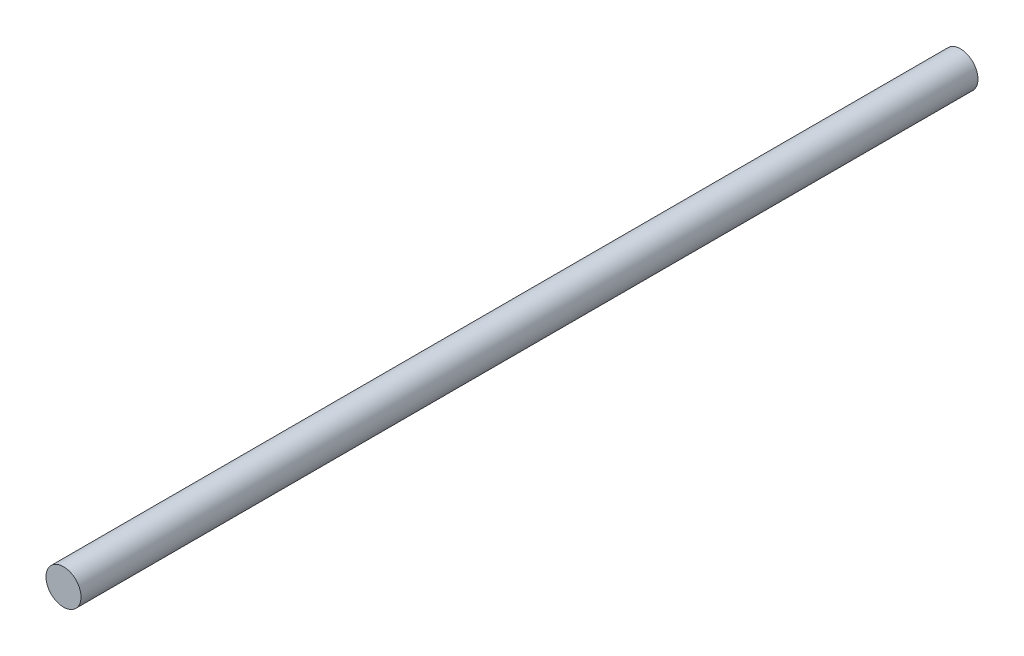
SolidWorks part; units mm, degrees
ref_plane "Alzado" through (0, 0, 0) normal (0, 0, 1) x (1, 0, 0)
ref_plane "Planta" through (0, 0, 0) normal (0, 1, 0) x (1, 0, 0)
ref_plane "Vista lateral" through (0, 0, 0) normal (1, 0, 0) x (0, 0, -1)
sketch "Croquis1" plane through (0, 0, 0) normal (0, 0, 1) x (1, 0, 0)
  circle A0 centre (0, 0) radius 12.7
  dimension "D1" = 25.4
extrude "Saliente-Extruir1" add sketch "Croquis1" along normal blind 650
